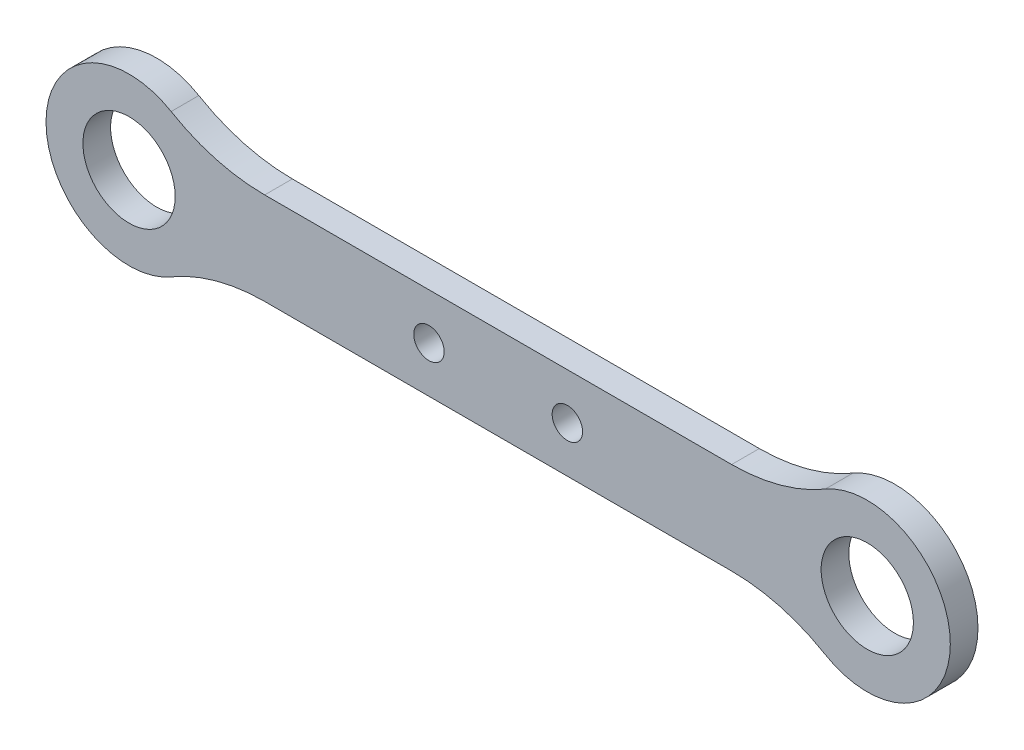
SolidWorks part; units mm, degrees
ref_plane "Plano frontal" through (0, 0, 0) normal (0, 0, 1) x (1, 0, 0)
ref_plane "Plano superior" through (0, 0, 0) normal (0, 1, 0) x (1, 0, 0)
ref_plane "Plano direito" through (0, 0, 0) normal (1, 0, 0) x (0, 0, -1)
sketch "Esboço1" plane through (0, 0, 0) normal (0, 0, 1) x (1, 0, 0)
  line L0 (7.4833, -5) -> (72.5167, -5)
  line L1 (0, 0) -> (80, 0) construction
  line L2 (7.4833, 5) -> (72.5167, 5)
  line L3 (0, 5) -> (80, 5) construction
  line L4 (0, -5) -> (80, -5) construction
  line L5 (40, 5) -> (40, -5) construction
  line L7 (0, 0) -> (80, 0) construction
  circle A0 centre (0, 0) radius 5
  circle A1 centre (32.5, 0) radius 1.65
  circle A2 centre (0, 0) radius 5
  arc A3 (7.4833, 5) -> (7.4833, -5) centre (0, 0) ccw
  circle A4 centre (47.5, 0) radius 1.65
  circle A5 centre (0, 0) radius 5
  circle A8 centre (0, 0) radius 5
  circle A9 centre (80, 0) radius 5
  circle A11 centre (0, 0) radius 5
  circle A13 centre (0, 0) radius 5
  circle A16 centre (80, 0) radius 5
  circle A18 centre (80, 0) radius 5
  circle A20 centre (80, 0) radius 5
  arc A22 (72.5167, 5) -> (72.5167, -5) centre (80, 0) cw
  circle A23 centre (80, 0) radius 5
  circle A25 centre (80, 0) radius 5
  point P14 (40, 0)
  point P32 (0, 0)
  dimension "D1" = 10
  dimension "D3" = 3.3
  dimension "D4" = 32.5
  dimension "D6" = 6
  dimension "D8" = 18
  dimension "D2" = 5
  dimension "D5" = 5
  dimension "D7" = 40
  dimension "D9" = 15
extrude "Ressalto-extrusão1" add sketch "Esboço1" along normal blind 3
fillet "Filete1" radius 20 4 edges at (7.4833, -5, 1.5) (72.5167, -5, 1.5) (72.5167, 5, 1.5) (7.4833, 5, 1.5)
